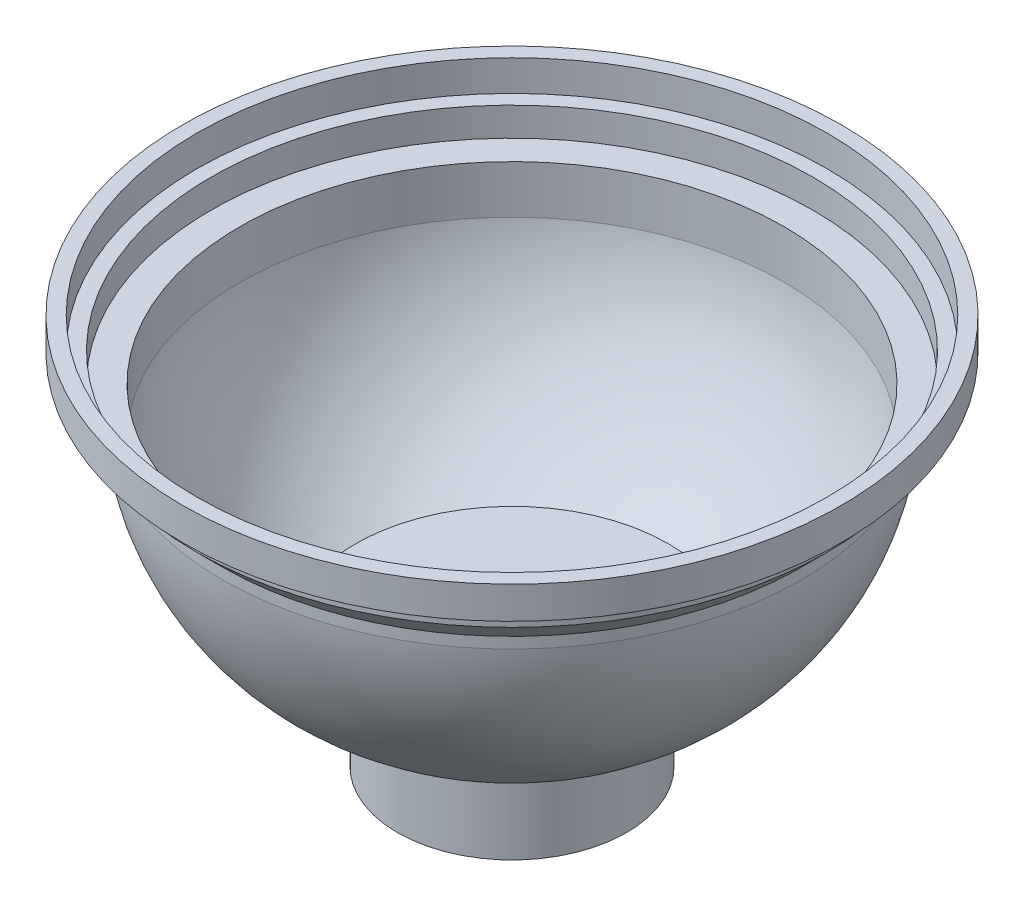
SolidWorks part; units mm, degrees
ref_plane "Plan de face" through (0, 0, 0) normal (0, 0, 1) x (1, 0, 0)
ref_plane "Plan de dessus" through (0, 0, 0) normal (0, 1, 0) x (1, 0, 0)
ref_plane "Plan de droite" through (0, 0, 0) normal (1, 0, 0) x (0, 0, -1)
sketch "Esquisse1" plane through (0, 0, 0) normal (0, 0, 1) x (1, 0, 0)
  line L0 (0, 50.4636) -> (0, 0) construction
  line L1 (0, 0) -> (30, 0) construction
  line L2 (30, 35) -> (30, 0)
  line L3 (30, 0) -> (40, 0)
  line L4 (40, 0) -> (40, 30)
  line L5 (40, 30) -> (45.779, 30)
  line L6 (30, 35) -> (15, 35)
  line L7 (15, 35) -> (15, 40)
  line L8 (15, 40) -> (54.5921, 40)
  line L9 (95, 98.7918) -> (95, 115.6087)
  line L10 (95, 115.6087) -> (105, 115.6087)
  line L11 (105, 115.6087) -> (105, 125.6087)
  line L12 (105, 125.6087) -> (110, 125.6087)
  line L13 (110, 125.6087) -> (110, 136.3911)
  line L14 (110, 136.3911) -> (115, 136.3911)
  line L15 (115, 136.3911) -> (115, 125.1526)
  line L16 (115, 125.1526) -> (110.3377, 125.1526)
  line L17 (110.3377, 125.1526) -> (110.3377, 120.0469)
  line L18 (110.3377, 120.0469) -> (100.9981, 110.7073)
  line L19 (100.9981, 110.7073) -> (100.9981, 106.8896)
  arc A0 (54.5921, 40) -> (95, 98.7918) centre (11.2125, 113.0973) ccw
  arc A1 (45.779, 30) -> (100.9981, 106.8896) centre (11.2125, 113.0973) ccw
  dimension "D7" = 5
  dimension "D11" = 85
  dimension "D1" = 40
  dimension "D2" = 30
  dimension "D3" = 30
  dimension "D4" = 35
  dimension "D5" = 10
  dimension "D6" = 10
  dimension "D8" = 5
  dimension "D9" = 5
  dimension "D10" = 5
  dimension "D12" = 15
  dimension "D13" = 110
revolve "Révolution1" add sketch "Esquisse1" angle 360 about L0
